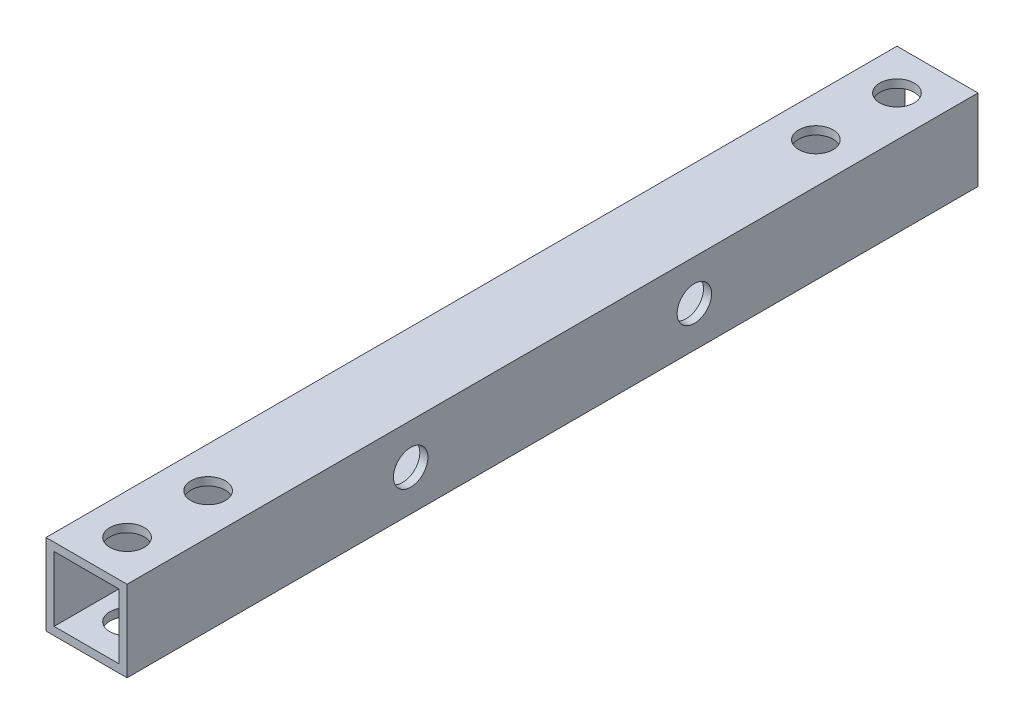
SolidWorks part; units mm, degrees
ref_plane "Front Plane" through (0, 0, 0) normal (0, 0, 1) x (1, 0, 0)
ref_plane "Top Plane" through (0, 0, 0) normal (0, 1, 0) x (1, 0, 0)
ref_plane "Right Plane" through (0, 0, 0) normal (1, 0, 0) x (0, 0, -1)
sketch "Sketch1" plane through (0, 0, 0) normal (0, 0, 1) x (1, 0, 0)
  line L0 (0, 0) -> (10, 0)
  line L1 (0, 0) -> (0, 10)
  line L2 (0, 10) -> (10, 10)
  line L3 (10, 0) -> (10, 10)
  line L4 (1, 9) -> (9, 9)
  line L5 (1, 9) -> (1, 1)
  line L6 (1, 1) -> (9, 1)
  line L7 (9, 9) -> (9, 1)
  dimension "D1" = 0
  dimension "D2" = 1
  dimension "D3" = 10
  dimension "D4" = 8
  dimension "D5" = 8
  dimension "D6" = 10
  dimension "D7" = 1
  dimension "D8" = 0
extrude "Boss-Extrude1" add sketch "Sketch1" along normal blind 105
sketch "Sketch2" plane through (0, 10, 0) normal (0, 1, 0) x (1, 0, 0)
  line L0 (10, 0) -> (0, 0) construction
  line L1 (10, -105) -> (10, 0) construction
  line L2 (10, -105) -> (0, -105) construction
  circle A0 centre (5, -5) radius 2.125
  circle A1 centre (5, -15) radius 2.125
  circle A2 centre (5, -100) radius 2.125
  circle A3 centre (5, -90) radius 2.125
  dimension "D1" = 4.25
  dimension "D2" = 4.25
  dimension "D3" = 5
  dimension "D5" = 5
  dimension "D6" = 5
  dimension "D7" = 4.25
  dimension "D8" = 4.25
  dimension "D9" = 5
  dimension "D10" = 5
  dimension "D11" = 5
  dimension "D12" = 15
  dimension "D4" = 15
extrude "Cut-Extrude1" cut sketch "Sketch2" against normal blind 116
sketch "Sketch4" plane through (10, 0, 0) normal (1, 0, 0) x (0, 0, -1)
  line L0 (0, 0) -> (0, 10) construction
  line L1 (-105, 0) -> (-105, 10) construction
  line L2 (-105, 10) -> (0, 10) construction
  circle A0 centre (-70, 5) radius 2.125
  circle A1 centre (-35, 5) radius 2.125
  dimension "D1" = 4.25
  dimension "D2" = 4.25
  dimension "D3" = 35
  dimension "D5" = 5
  dimension "D6" = 5
  dimension "D4" = 35
extrude "Cut-Extrude3" cut sketch "Sketch4" against normal blind 10
